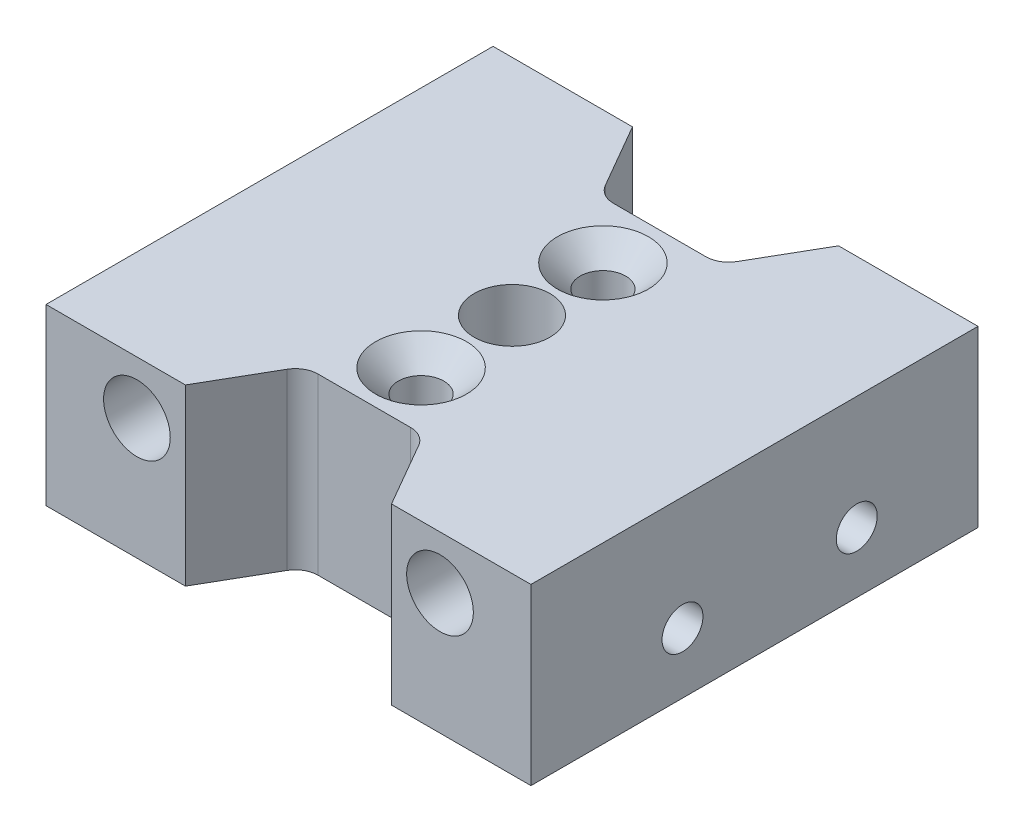
SolidWorks part; units mm, degrees
material "6061 合金"
ref_plane "前视基准面" through (0, 0, 0) normal (0, 0, 1) x (1, 0, 0)
ref_plane "上视基准面" through (0, 0, 0) normal (0, 1, 0) x (1, 0, 0)
ref_plane "右视基准面" through (0, 0, 0) normal (1, 0, 0) x (0, 0, -1)
sketch "草图1" plane through (0, 0, 0) normal (0, 0, 1) x (1, 0, 0)
  line L0 (163, -49.74) -> (-23.7584, -49.74) construction
  line L1 (2, -49.74) -> (34, -49.74)
  line L2 (2, -49.74) -> (2, -38.24)
  line L3 (2, -38.24) -> (34, -38.24)
  line L4 (34, -49.74) -> (34, -38.24)
  circle A0 centre (8, -41.74) radius 2.2
  circle A1 centre (28, -41.7379) radius 2.2
  dimension "D1" = 6
  dimension "D4" = 4.4
  dimension "D5" = 4.4
  dimension "D2" = 6
  dimension "D3" = 3.5
extrude "凸台-拉伸1" add sketch "草图1" along normal blind 29.5
sketch "草图2" plane through (0, -49.74, 0) normal (0, -1, 0) x (1, 0, 0)
  line L0 (2, 29.5) -> (34, 0) construction
  line L1 (34, 29.5) -> (2, 0) construction
  circle A0 centre (18, 14.75) radius 2.5
  dimension "D1" = 5
extrude "切除-拉伸1" cut sketch "草图2" against normal blind 29.5
sketch "草图3" plane through (0, -49.74, 0) normal (0, -1, 0) x (1, 0, 0)
  line L0 (18, 0) -> (18, 29.5) construction
  line L1 (2, 0) -> (34, 0) construction
  line L2 (2, 29.5) -> (34, 29.5) construction
  circle A0 centre (18, 8.75) radius 1.5
  circle A1 centre (18, 20.75) radius 1.5
  dimension "D1" = 12
  dimension "D2" = 8.75
  dimension "D3" = 3
  dimension "D4" = 3
extrude "切除-拉伸2" cut sketch "草图3" against normal blind 29.5
chamfer "倒角1" distance 1.5 angle 45 2 edges at (18, -38.24, 7.25) (18, -38.24, 19.25)
sketch "Sketch2" plane through (34, 0, 0) normal (1, 0, 0) x (0, 0, -1)
  line L0 (0, -45.74) -> (-29.5, -45.74) construction
  line L1 (0, -49.74) -> (0, -38.24) construction
  line L4 (-29.5, -49.74) -> (0, -49.74) construction
  circle A0 centre (-19.5, -45.74) radius 1.35
  circle A1 centre (-8, -45.74) radius 1.35
  dimension "D1" = 2.7
  dimension "D2" = 8
  dimension "D3" = 11.5
  dimension "D4" = 4
extrude "Cut-Extrude1" cut sketch "Sketch2" against normal blind 10
ref_plane "Plane1" through (18, 0, 0) normal (-1, 0, 0) x (0, 0, 1)
mirror "Mirror1" about plane through (18, 0, 0) normal (-1, 0, 0) of "Cut-Extrude1"
sketch "Sketch3" plane through (0, -38.24, 0) normal (0, 1, 0) x (1, 0, 0)
  line L0 (11.2, 0) -> (13.6537, -4.25)
  line L1 (34, 0) -> (2, 0) construction
  line L2 (14.9528, -5) -> (21.0472, -5)
  line L3 (22.3463, -4.25) -> (24.8, 0)
  line L4 (11.2, 0) -> (24.8, 0)
  line L5 (2, -14.75) -> (34, -14.75) construction
  line L6 (2, -29.5) -> (2, 0) construction
  line L7 (34, -29.5) -> (34, 0) construction
  line L8 (25.8, 0) -> (25.8, -29.5) construction
  line L9 (11.2, -29.5) -> (24.8, -29.5)
  line L10 (22.3463, -25.25) -> (24.8, -29.5)
  line L11 (14.9528, -24.5) -> (21.0472, -24.5)
  line L12 (11.2, -29.5) -> (13.6537, -25.25)
  arc A0 (22.3463, -25.25) -> (21.0472, -24.5) centre (21.0472, -26) ccw
  arc A1 (14.9528, -24.5) -> (13.6537, -25.25) centre (14.9528, -26) ccw
  arc A2 (21.0472, -5) -> (22.3463, -4.25) centre (21.0472, -3.5) ccw
  arc A3 (13.6537, -4.25) -> (14.9528, -5) centre (14.9528, -3.5) ccw
  point P20 (21.9132, -24.5)
  point P23 (14.0868, -24.5)
  point P26 (21.9132, -5)
  point P29 (14.0868, -5)
  dimension "D6" = 1.5
  dimension "D1" = 60
  dimension "D2" = 60
  dimension "D3" = 1
  dimension "D4" = 9.2
  dimension "D5" = 5
extrude "Extrude1" cut sketch "Sketch3" against normal blind 25
